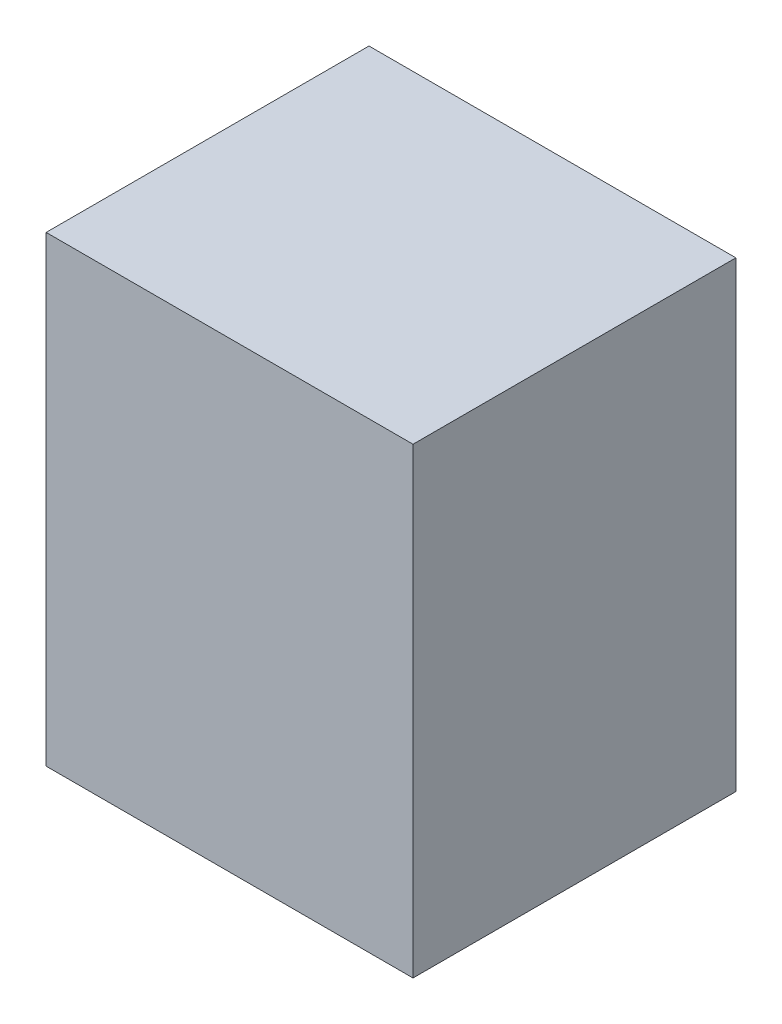
SolidWorks part; units mm, degrees
material "Polyurethane Foam Flexible"
ref_plane "Front Plane" through (0, 0, 0) normal (0, 0, 1) x (1, 0, 0)
ref_plane "Top Plane" through (0, 0, 0) normal (0, 1, 0) x (1, 0, 0)
ref_plane "Right Plane" through (0, 0, 0) normal (1, 0, 0) x (0, 0, -1)
sketch "Sketch1" plane through (0, 0, 0) normal (0, 1, 0) x (1, 0, 0)
  line L1 (0, 0) -> (127, 0)
  line L2 (0, 0) -> (0, 111.76)
  line L3 (0, 111.76) -> (127, 111.76)
  line L4 (127, 0) -> (127, 111.76)
  dimension "D1" = 127
  dimension "D2" = 111.76
extrude "Boss-Extrude1" add sketch "Sketch1" along normal blind 160.02 contours L2 L3 L4 L1
